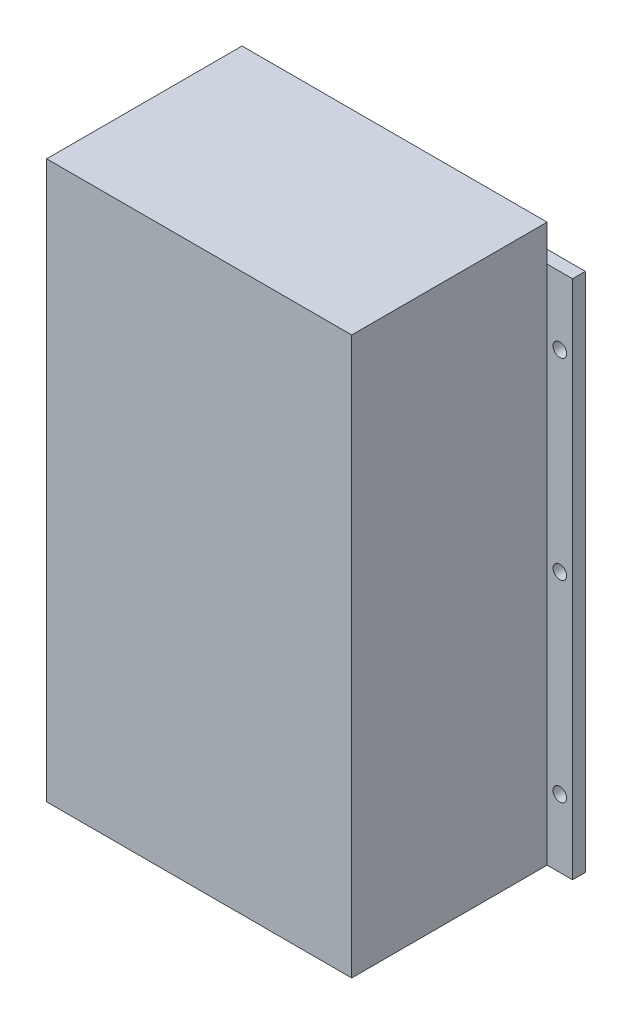
SolidWorks part; units mm, degrees
ref_plane "Front Plane" through (0, 0, 0) normal (0, 0, 1) x (1, 0, 0)
ref_plane "Top Plane" through (0, 0, 0) normal (0, 1, 0) x (1, 0, 0)
ref_plane "Right Plane" through (0, 0, 0) normal (1, 0, 0) x (0, 0, -1)
sketch "Sketch2" plane through (0, 0, 0) normal (0, 0, 1) x (1, 0, 0)
  line L1 (0, 0) -> (126, 0)
  line L2 (0, 0) -> (0, 215)
  line L3 (0, 215) -> (126, 215)
  line L4 (126, 0) -> (126, 215)
  dimension "D1" = 126
  dimension "D2" = 215
extrude "Boss-Extrude1" add sketch "Sketch2" along normal blind 86
sketch "Sketch3" plane through (126, 0, 0) normal (1, 0, 0) x (0, 0, -1)
  line L0 (-86, 0) -> (0, 0) construction
  line L1 (0, 215) -> (-5.3, 215)
  line L2 (0, 215) -> (0, 0)
  line L3 (0, 0) -> (-5.3, 0)
  line L4 (-5.3, 215) -> (-5.3, 0)
  dimension "D1" = 5.3
extrude "Boss-Extrude2" add sketch "Sketch3" along normal blind 10.5 and the other way blind 136.5
sketch "Sketch5" plane through (0, 0, 5.3) normal (0, 0, 1) x (1, 0, 0)
  line L0 (131.25, 215) -> (131.25, 0) construction
  line L1 (126, 215) -> (136.5, 215) construction
  line L2 (126, 0) -> (136.5, 0) construction
  circle A0 centre (131.25, 28) radius 2.8
  dimension "D1" = 28
sketch "Sketch6" plane through (0, 0, 5.3) normal (0, 0, 1) x (1, 0, 0)
  line L0 (131.25, 215) -> (131.25, 0) construction
  circle A0 centre (131.25, 107.5) radius 2.8
extrude "Cut-Extrude1" cut sketch "Sketch5" against normal blind 10.5
extrude "Cut-Extrude2" cut sketch "Sketch6" against normal blind 10.5
sketch "Sketch7" plane through (0, 0, 5.3) normal (0, 0, 1) x (1, 0, 0)
  line L0 (131.25, 215) -> (131.25, -21.2328) construction
  line L1 (126, 215) -> (136.5, 215) construction
  circle A0 centre (131.25, 187) radius 2.8
  dimension "D1" = 28
extrude "Cut-Extrude3" cut sketch "Sketch7" against normal blind 10.5
pattern_linear "LPattern1" count 2 spacing 136.5 along (-1, 0, 0) of "Cut-Extrude1", "Cut-Extrude2", "Cut-Extrude3"
sketch "Sketch8" plane through (0, 215, 0) normal (0, 1, 0) x (1, 0, 0)
  line L1 (0, -5.3) -> (126, -5.3)
  line L2 (0, -5.3) -> (0, -86)
  line L3 (0, -86) -> (126, -86)
  line L4 (126, -5.3) -> (126, -86)
extrude "Boss-Extrude3" add sketch "Sketch8" along normal blind 15
